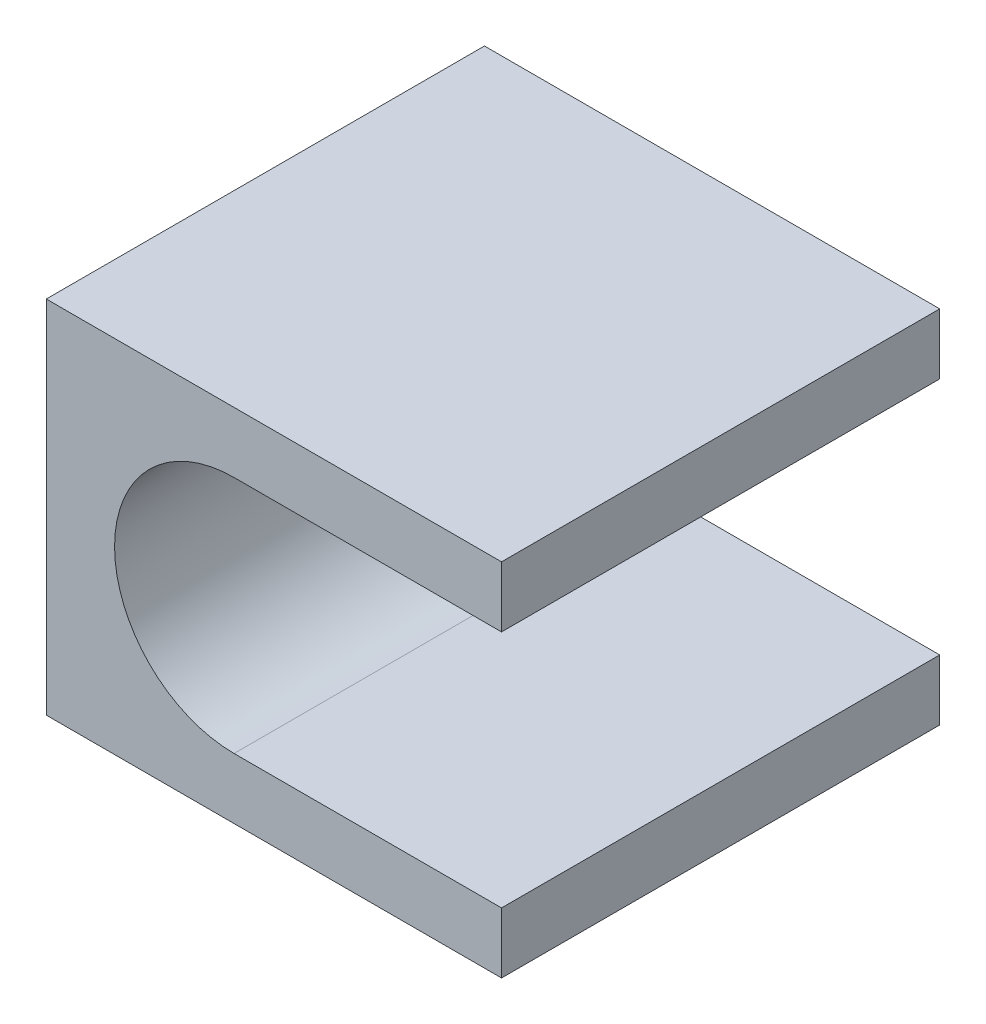
SolidWorks part; units mm, degrees
other "标注1"
sketch "草图10" plane through (24, 9.5, 31.5) normal (0.9281, 0.3391, 0.154) x (-0.3723, 0.8344, 0.4063)
other "标注2"
sketch "草图11" plane through (24, 9.5, 31.5) normal (0.9281, 0.3391, 0.154) x (-0.3723, 0.8344, 0.4063)
ref_plane "前视基准面" through (0, 0, 0) normal (1, 0, 0) x (0, 1, 0)
ref_plane "上视基准面" through (0, 0, 0) normal (0, 0, 1) x (0, 1, 0)
ref_plane "右视基准面" through (0, 0, 0) normal (0, 1, 0) x (-1, 0, 0)
other "Configuration Table"
sketch "1底部方形_24x19" plane through (0, 0, 0) normal (0, 0, 1) x (0, 1, 0)
  line L1 (-9.5, 12) -> (9.5, 12)
  line L2 (-9.5, 12) -> (-9.5, -12)
  line L3 (-9.5, -12) -> (9.5, -12)
  line L4 (9.5, 12) -> (9.5, -12)
  line L5 (0, -12) -> (0, 12) construction
  line L6 (-9.5, 0) -> (9.5, 0) construction
  point P0 (0, 0)
  dimension "D1" = 19
  dimension "D2" = 24
extrude "1凸台-拉伸_高33" add sketch "1底部方形_24x19" along normal blind 33
sketch "2吸嘴停靠渐变槽" plane through (0, 0, 33) normal (0, 0, 1) x (1, 0, 0)
  line L0 (12, -9.5) -> (12, 9.5) construction
  line L1 (-12, 9.5) -> (-12, -9.5) construction
  line L2 (12, -5.1) -> (12, 5.1)
  line L3 (-12, 9.5) -> (-12, -9.5) construction
  line L4 (-12, 0) -> (12, 0) construction
  line L5 (-1.9, 5.1) -> (12, 5.1)
  line L6 (-1.9, -5.1) -> (12, -5.1)
  line L7 (-5.2139, -3.8302) -> (-2, 0) construction
  line L8 (-5.2139, 3.8302) -> (-2, 0) construction
  line L9 (-4.0554, -4.6222) -> (-1.9, 0) construction
  line L10 (-1.9, 0) -> (-4.0554, 4.6222) construction
  arc A0 (-1.9, 5.1) -> (-1.9, -5.1) centre (-1.9, 0) ccw construction
  arc A1 (-5.2139, 3.8302) -> (-5.2139, -3.8302) centre (-2, 0) ccw
  circle A2 centre (-1.9, 0) radius 5.1 construction
  spline S0 degree 2 poles (-5.2139, 3.8302) (-3.8291, 5.0932) (-1.9, 5.1) knots 0 0 0 1 1 1
  spline S1 degree 2 poles (-5.2139, -3.8302) (-3.8291, -5.0932) (-1.9, -5.1) knots 0 0 0 1 1 1
  point P7 (-7, 0)
  point P14 (-5.2139, 3.8302)
  point P15 (-4.0554, 4.6222)
  point P16 (-4.0554, -4.6222)
  point P17 (-5.2139, -3.8302)
  dimension "D1" = 10.2
  dimension "D4" = 10
  dimension "D2" = 5
  dimension "D3" = 10.1
  dimension "D5" = 0.1
  dimension "D6" = 50
  dimension "D7" = 50
  dimension "D8" = 65
  dimension "D9" = 65
  dimension "D10" = 10.2
extrude "2切除-拉伸" cut sketch "2吸嘴停靠渐变槽" against normal up to next
ref_plane "3基准面1" through (0, 0, 25) normal (0, 0, 1) x (1, 0, 0)
sketch "4反光板停靠槽" plane through (0, 0, 25) normal (0, 0, 1) x (1, 0, 0)
  line L18 (-12, 9.5) -> (12, 9.5) construction
  line L22 (-0.7, 8.4) -> (12, 8.4)
  line L23 (12, -9.5) -> (12, 9.5) construction
  line L24 (-0.7, -8.4) -> (12, -8.4)
  line L25 (12, 8.4) -> (12, -8.4)
  line L27 (12, 0) -> (-12, 0) construction
  line L28 (-12, -9.5) -> (12, -9.5) construction
  arc A2 (-0.7, 8.4) -> (-0.7, -8.4) centre (-2, 0) ccw
  arc A5 (-5.2139, 3.8302) -> (-5.2139, -3.8302) centre (-2, 0) ccw construction
  arc A6 (-5.2139, 3.8302) -> (-5.2139, -3.8302) centre (-2, 0) ccw construction
  dimension "D1" = 9.5
  dimension "D2" = 17
  dimension "D5" = 8.4
  dimension "D6" = 5
  dimension "D7" = 9.5
  dimension "D3" = 16.8
  dimension "D4" = 8.4
extrude "4切除-拉伸2" cut sketch "4反光板停靠槽" against normal blind 1.9 contours L22 L25 L24 A2
ref_plane "5基准面_反光板下表面" through (0, 0, 23.1) normal (0, 0, 1) x (1, 0, 0)
sketch "6反光板小圆柱" plane through (0, 0, 23.1) normal (0, 0, 1) x (1, 0, 0)
  line L1 (-2.1, -6.3) -> (12, -6.3)
  line L5 (-2.1, 5.1) -> (-2.1, -5.1) construction
  line L6 (-2.1, 6.3) -> (12, 6.3)
  line L7 (12, 5.1) -> (12, 9.5) construction
  line L8 (12, 6.3) -> (12, -6.3)
  arc A2 (-2.1, 6.3) -> (-2.1, -6.3) centre (-2.1, 0) ccw
  point P0 (-2.1, 0)
  point P2 (-2, 0)
  point P13 (12, 0)
  dimension "D1" = 6.3
  dimension "D3" = 0.1
  dimension "D2" = 12.6
  dimension "D4" = 6.3
extrude "6切除-拉伸3" cut sketch "6反光板小圆柱" against normal up to next
sketch "7草图5" plane through (0, 0, 0) normal (0, 0, -1) x (1, 0, 0)
  line L0 (12, -9.5) -> (-12, -9.5) construction
  line L1 (-12, -9.5) -> (-12, 9.5) construction
  line L2 (-12, 9.5) -> (12, 9.5) construction
  line L3 (12, -9.5) -> (-12, -9.5)
  line L4 (-12, -9.5) -> (-12, 9.5)
  line L5 (-12, 9.5) -> (12, 9.5)
  line L6 (12, 9.5) -> (12, -9.5)
extrude "7凸台-拉伸_底板厚度" add sketch "7草图5" against normal blind 5
sketch "8中轴面" plane through (-12, 0, 0) normal (-1, 0, 0) x (0, -1, 0)
  line L0 (0, 33) -> (0, 0) construction
  line L1 (-9.5, 33) -> (9.5, 33) construction
  line L2 (-9.5, 0) -> (9.5, 0) construction
ref_plane "9中轴基准面" through (0, 0, 0) normal (0, 1, 0) x (1, 0, 0)
sketch "10设计脱离斜坡" plane through (0, 9.5, 0) normal (0, 1, 0) x (-1, 0, 0)
  line L2 (-12, 33) -> (-12, 0) construction
  line L3 (12, 33) -> (12, 0) construction
  line L5 (-12, 31.1627) -> (-12, 33)
  line L6 (10.45, 25) -> (-10.45, 25) construction
  line L9 (9, 33) -> (-12, 33)
  line L10 (-12, 31.1627) -> (9, 33)
  line L11 (-12, 33) -> (12, 33) construction
  dimension "D1" = 5
  dimension "D2" = 3
  dimension "D3" = 1.8373
  dimension "D4" = 24
  dimension "D5" = 6.1627
extrude "10切除-拉伸4" cut sketch "10设计脱离斜坡" against normal up to surface (19 mm away) up to face at (0, -9.5, 16.5)
sketch "11磁铁高度" plane through (-12, 0, 0) normal (-1, 0, 0) x (0, -1, 0)
  line L0 (-9.5, 33) -> (-9.5, 0) construction
  line L1 (-9.5, 28.5) -> (-1, 28.5)
  line L2 (-9.5, 28.5) -> (-9.5, 25.4)
  line L3 (-9.5, 25.4) -> (-1, 25.4)
  line L4 (9.5, 28.5) -> (9.5, 25.4)
  line L5 (-9.5, 28.5) -> (9.5, 25.4) construction
  line L6 (-9.5, 25.4) -> (9.5, 28.5) construction
  line L7 (9.5, 33) -> (9.5, 0) construction
  line L8 (-1, 28.5) -> (-1, 25.4)
  line L9 (1, 28.5) -> (1, 25.4)
  line L10 (1, 28.5) -> (9.5, 28.5)
  line L11 (1, 25.4) -> (9.5, 25.4)
  line L15 (9.5, 0) -> (-9.5, 0) construction
  point P4 (0, 26.95)
  dimension "D1" = 28.5
  dimension "D2" = 3.1
  dimension "D3" = 1
  dimension "D4" = 1
extrude "11切除-拉伸5" cut sketch "11磁铁高度" against normal blind 4.9
sketch "11d1_磁铁开窗" plane through (-12, 0, 0) normal (-1, 0, 0) x (0, -1, 0)
  line L0 (1, 25.4) -> (9.5, 25.4) construction
  line L5 (-1, 28.5) -> (1, 25.4) construction
  line L7 (1, 28.5) -> (1, 25.4) construction
  line L8 (9.5, 28.5) -> (1, 28.5) construction
  line L9 (-3, 25.4) -> (3, 25.4)
  line L10 (-3, 25.4) -> (-3, 28.5)
  line L11 (-3, 28.5) -> (3, 28.5)
  line L12 (3, 25.4) -> (3, 28.5)
  line L13 (0, 28.5) -> (0, 25.4) construction
  line L14 (-3, 26.95) -> (3, 26.95) construction
  point P10 (0, 26.95)
  dimension "D1" = 6
extrude "11d1切除-拉伸6" cut sketch "11d1_磁铁开窗" against normal blind 10
sketch "12切除薄壁" plane through (0, 0, 25.4) normal (0, 0, 1) x (1, 0, 0)
  line L43 (-0.7, 8.4) -> (-0.7, -8.4)
  arc A0 (-0.7, 8.4) -> (-0.7, -8.4) centre (-2, 0) ccw construction
  arc A7 (-0.7, 8.4) -> (-0.7, -8.4) centre (-2, 0) ccw
extrude "12切除-拉伸9" cut sketch "12切除薄壁" against normal up to next
sketch "螺丝安装孔" plane through (0, 0, 5) normal (0, 0, 1) x (1, 0, 0)
  line L0 (13.2, 0) -> (-13.2, 0) construction
  line L1 (12, 6.3) -> (12, -6.3) construction
  circle A0 centre (2, 0) radius 3.5
  dimension "D1" = 10
  dimension "D2" = 7
sketch "设计内套槽" plane through (0, 0, 33) normal (0, 0, 1) x (1, 0, 0)
  line L0 (-2.1, 6.5) -> (12, 6.5)
  line L2 (-2.1, -6.5) -> (12, -6.5)
  line L4 (12, 6.5) -> (12, -6.5)
  line L5 (12, -9.5) -> (12, 9.5) construction
  arc A1 (-1.4745, -4.9607) -> (-1.4745, 4.9607) centre (-2.1, 0) ccw construction
  arc A2 (-2.1, 6.5) -> (-2.1, -6.5) centre (-2.1, 0) ccw
  point P4 (-2.1, 0)
  point P8 (-2, 0)
  dimension "D1" = 13
  dimension "D4" = 6.5
  dimension "D6" = 5
  dimension "D5" = 0.1
  dimension "D2" = 6.5
  dimension "D3" = 6.5
extrude "切除-拉伸11" cut sketch "设计内套槽" against normal blind 3.5 contours L0 A2 L2 L4
sketch "实际高度" plane through (0, 0, 33) normal (0, 0, 1) x (1, 0, 0)
  line L0 (-9, -9.5) -> (-9, 9.5) construction
  line L1 (41.98, 9.5) -> (-12, 9.5)
  line L2 (41.98, 9.5) -> (41.98, -9.5)
  line L3 (41.98, -9.5) -> (-12, -9.5)
  line L4 (-12, 9.5) -> (-12, -9.5)
  line L5 (41.98, 9.5) -> (-12, -9.5) construction
  line L6 (41.98, -9.5) -> (-12, 9.5) construction
  line L7 (-9, 9.5) -> (-12, 9.5) construction
  point P4 (14.99, 0)
  dimension "D1" = 23.99
extrude "切除-拉伸12" cut sketch "实际高度" against normal blind 1
sketch "实际脱离斜坡" plane through (0, -9.5, 0) normal (0, -1, 0) x (1, 0, 0)
  line L0 (2.4301, 32) -> (12, 31.1627) construction
  line L1 (2.4301, 32) -> (12, 31.1627)
  line L3 (-6, 32) -> (12, 28.8261)
  line L5 (-12, 32) -> (2.4301, 32) construction
  line L6 (12, 31.1627) -> (12, 0) construction
  line L7 (10.45, 25) -> (-10.45, 25) construction
  line L9 (-12, 33) -> (-12, 0) construction
  line L11 (12, 28.8261) -> (12, 31.1627)
  line L12 (2.4301, 32) -> (-6, 32)
  dimension "D1" = 6
  dimension "D2" = 10
  dimension "D3" = 3.8261
  dimension "D4" = 3.1739
  dimension "D5" = 18
extrude "切除-拉伸13" cut sketch "实际脱离斜坡" against normal through all
extrude "切除-拉伸15" cut sketch "螺丝安装孔" against normal up to next contours A0
sketch "退刀中心位置" plane through (0, 0, 5) normal (0, 0, 1) x (1, 0, 0)
  line L0 (12, -9.5) -> (12, 9.5) construction
  line L1 (12, -9.5) -> (12, 9.5) construction
  line L2 (12, 0) -> (-12, 0) construction
  line L3 (27.5479, 0) -> (-12, 0) construction
  line L4 (13.2, 0) -> (-13.2, 0) construction
  line L5 (20, 0) -> (20, -11.3299) construction
  circle A0 centre (20, 0) radius 8 construction
  dimension "D2" = 16
  dimension "D1" = 8
sketch "反光板槽_补缺" plane through (0, 0, 25.4) normal (0, 0, -1) x (1, 0, 0)
  line L0 (-7.1, -3) -> (-7.1, -6.8) construction
  line L1 (-0.7, -8.4) -> (-0.7, -5.1) construction
  line L2 (-0.7, -5.1) -> (-1.9, -5.1) construction
  line L3 (-6, -3) -> (-7.1, -3) construction
  line L4 (-7.1, 3) -> (-6, 3) construction
  line L5 (-1.9, 5.1) -> (-0.7, 5.1) construction
  line L6 (-0.7, 5.1) -> (-0.7, 8.4) construction
  line L7 (-7.1, 6.8) -> (-7.1, 3) construction
  line L8 (-7.1, -3) -> (-7.1, -6.8)
  line L9 (-0.7, -8.4) -> (-0.7, -5.1)
  line L10 (-0.7, -5.1) -> (-1.9, -5.1)
  line L11 (-6, -3) -> (-7.1, -3)
  line L12 (-7.1, 3) -> (-6, 3)
  line L13 (-1.9, 5.1) -> (-0.7, 5.1)
  line L14 (-0.7, 5.1) -> (-0.7, 8.4)
  line L15 (-7.1, 6.8) -> (-7.1, 3)
  arc A0 (-7.1, -6.8) -> (-0.7, -8.4) centre (-2, 0) ccw construction
  arc A1 (-6, -3) -> (-5.2139, -3.8302) centre (-2, 0) ccw construction
  arc A2 (-5.2139, 3.8302) -> (-6, 3) centre (-2, 0) ccw construction
  arc A3 (-0.7, 8.4) -> (-7.1, 6.8) centre (-2, 0) ccw construction
  arc A4 (-7.1, -6.8) -> (-0.7, -8.4) centre (-2, 0) ccw
  arc A5 (-6, -3) -> (-5.2139, -3.8302) centre (-2, 0) ccw
  arc A6 (-5.2139, 3.8302) -> (-6, 3) centre (-2, 0) ccw
  arc A7 (-0.7, 8.4) -> (-7.1, 6.8) centre (-2, 0) ccw
  parabola Q0 (-1.9, -5.1) -> (-5.2139, -3.8302) focus (-2.9632, -2.5982) apex (-3.8759, -4.7046) construction
  parabola Q1 (-5.2139, 3.8302) -> (-1.9, 5.1) focus (-2.9632, 2.5982) apex (-3.8759, 4.7046) construction
  parabola Q2 (-1.9, -5.1) -> (-5.2139, -3.8302) focus (-2.9632, -2.5982) apex (-3.8759, -4.7046)
  parabola Q3 (-5.2139, 3.8302) -> (-1.9, 5.1) focus (-2.9632, 2.5982) apex (-3.8759, 4.7046)
extrude "凸台-拉伸2" add sketch "反光板槽_补缺" along normal up to surface (0.4 mm away) up to face at (5.65, 6.75, 25)
sketch "磁铁宽度挡板" plane through (0, -9.5, 0) normal (0, -1, 0) x (1, 0, 0)
  line L0 (-7.1, 25.4) -> (-12, 25.4) construction
  line L1 (-12, 28.5) -> (-11.2, 28.5)
  line L2 (-12, 28.5) -> (-12, 25.4)
  line L3 (-12, 25.4) -> (-11.2, 25.4)
  line L4 (-11.2, 28.5) -> (-11.2, 25.4)
  line L5 (-12, 28.5) -> (-11.2, 25.4) construction
  line L6 (-12, 25.4) -> (-11.2, 28.5) construction
  line L7 (-7.1, 25.4) -> (-7.1, 28.5) construction
  point P4 (-11.6, 26.95)
  dimension "D1" = 4.1
  dimension "D2" = 0.8
extrude "凸台-拉伸3" add sketch "磁铁宽度挡板" against normal up to surface (19 mm away) up to face at (-4.9111, 9.5, 22.2918)
sketch "草图13" plane through (0, 0, 5) normal (0, 0, 1) x (1, 0, 0)
  line L3 (-2.1, -6.3) -> (12, -6.3)
  line L4 (12, -6.3) -> (12, 6.3)
  line L5 (12, 6.3) -> (-2.1, 6.3)
  line L6 (-2.1, -6.3) -> (12, -6.3)
  line L7 (12, -6.3) -> (12, 6.3)
  line L8 (12, 6.3) -> (-2.1, 6.3)
  arc A1 (-2.1, 6.3) -> (-2.1, -6.3) centre (-2.1, 0) ccw
  arc A2 (-2.1, 6.3) -> (-2.1, -6.3) centre (-2.1, 0) ccw
  dimension "D1" = 0
extrude "切除-拉伸16" cut sketch "草图13" against normal through all
sketch "草图14" plane through (0, 0, 23.1) normal (0, 0, 1) x (1, 0, 0)
  line L0 (12, -9.5) -> (12, 9.5) construction
  line L1 (-12, -9.5) -> (-12, 9.5) construction
  line L2 (-12, -9.5) -> (12, -9.5) construction
  line L3 (-12, 9.5) -> (12, 9.5) construction
  line L4 (12, -9.5) -> (12, 9.5)
  line L5 (-12, -9.5) -> (-12, 9.5)
  line L6 (-12, -9.5) -> (12, -9.5)
  line L7 (-12, 9.5) -> (12, 9.5)
extrude "切除-拉伸19" cut sketch "草图14" along normal through all
